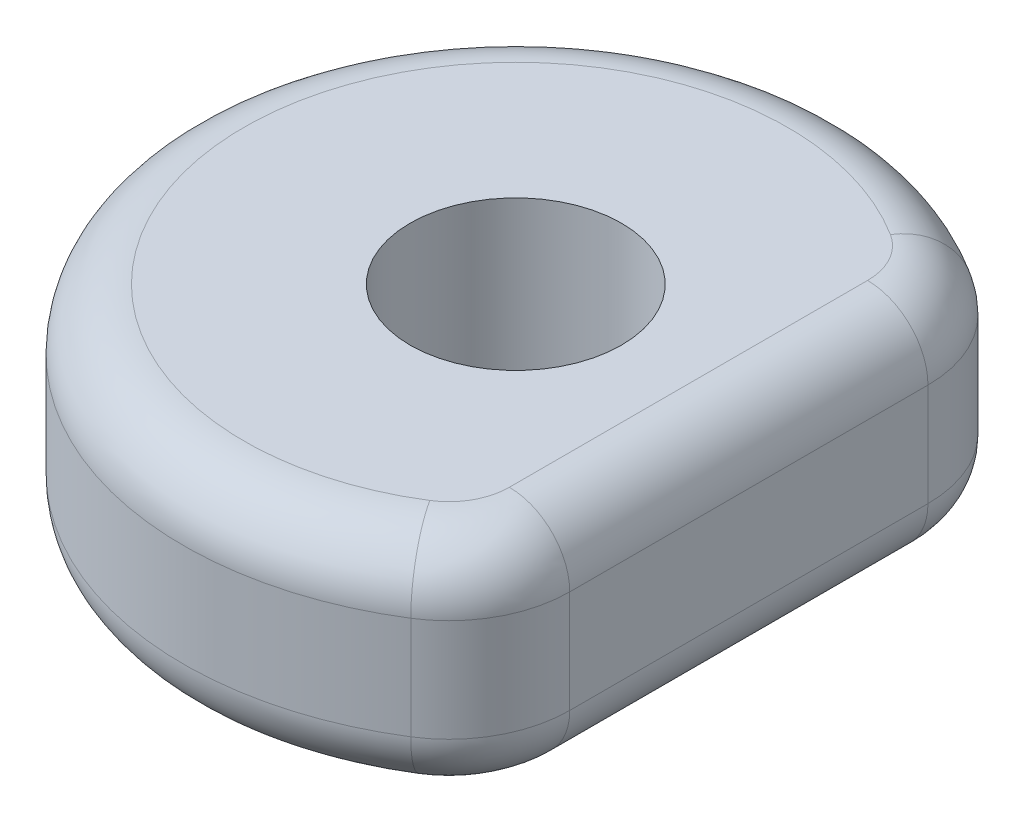
SolidWorks part; units mm, degrees
ref_plane "Alzado" through (0, 0, 0) normal (0, 0, 1) x (1, 0, 0)
ref_plane "Planta" through (0, 0, 0) normal (0, 1, 0) x (1, 0, 0)
ref_plane "Vista lateral" through (0, 0, 0) normal (1, 0, 0) x (0, 0, -1)
sketch "Croquis1" plane through (0, 0, 0) normal (0, 1, 0) x (1, 0, 0)
  line L0 (3.859, 3.919) -> (3.859, -3.919)
  circle A0 centre (0, 0) radius 1.75
  arc A2 (3.859, 3.919) -> (3.859, -3.919) centre (0, 0) ccw
  circle A3 centre (0, 0) radius 5.5 construction
  dimension "D1" = 3.5
  dimension "D2" = 11
extrude "Saliente-Extruir1" add sketch "Croquis1" along normal blind 3.7
fillet "Redondeo1" radius 2 2 edges at (3.859, 1.85, -3.919) (3.859, 1.85, 3.919)
fillet "Redondeo2" radius 1 8 edges at (3.6089, 0, -3.9339) (3.859, 0, 0) (3.6089, 0, 3.9339) (-5.5, 0, 0) (3.6089, 3.7, -3.9339) (3.859, 3.7, 0) (3.6089, 3.7, 3.9339) (-5.5, 3.7, 0)
